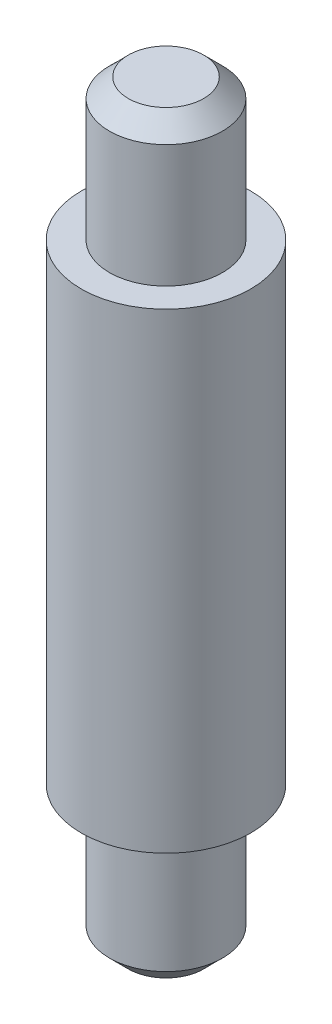
SolidWorks part; units mm, degrees
ref_plane "Front Plane" through (0, 0, 0) normal (0, 0, 1) x (1, 0, 0)
ref_plane "Top Plane" through (0, 0, 0) normal (0, 1, 0) x (1, 0, 0)
ref_plane "Right Plane" through (0, 0, 0) normal (1, 0, 0) x (0, 0, -1)
sketch "Sketch1" plane through (0, 0, 0) normal (0, 1, 0) x (1, 0, 0)
  circle A0 centre (0, 0) radius 9
  dimension "D1" = 18
extrude "Boss-Extrude1" add sketch "Sketch1" along normal mid plane 50
sketch "Sketch2" plane through (0, 0, 0) normal (0, 1, 0) x (1, 0, 0)
  circle A0 centre (0, 0) radius 6
  dimension "D1" = 12
extrude "Boss-Extrude2" add sketch "Sketch2" along normal mid plane 80
chamfer "Chamfer1" distance 2 angle 45 2 edges at (0, -40, 6) (0, 40, 6)
